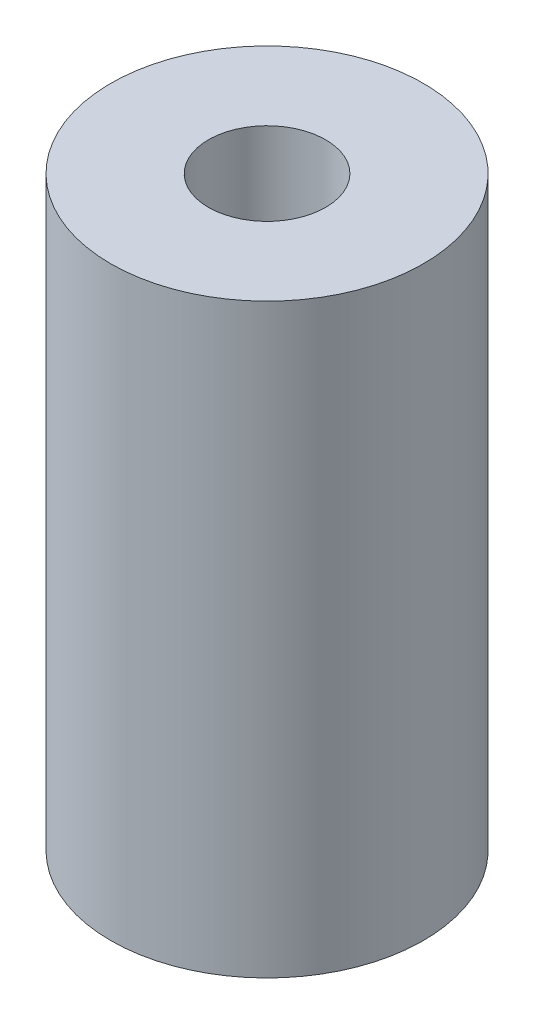
SolidWorks part; units mm, degrees
ref_plane "Front Plane" through (0, 0, 0) normal (0, 0, 1) x (1, 0, 0)
ref_plane "Top Plane" through (0, 0, 0) normal (0, 1, 0) x (1, 0, 0)
ref_plane "Right Plane" through (0, 0, 0) normal (1, 0, 0) x (0, 0, -1)
sketch "Sketch2" plane through (0, 0, 0) normal (0, 1, 0) x (1, 0, 0)
  circle A0 centre (0, 0) radius 4
  circle A1 centre (0, 0) radius 1.5
extrude "Boss-Extrude2" add sketch "Sketch2" along normal blind 15 contours A0 | A1
